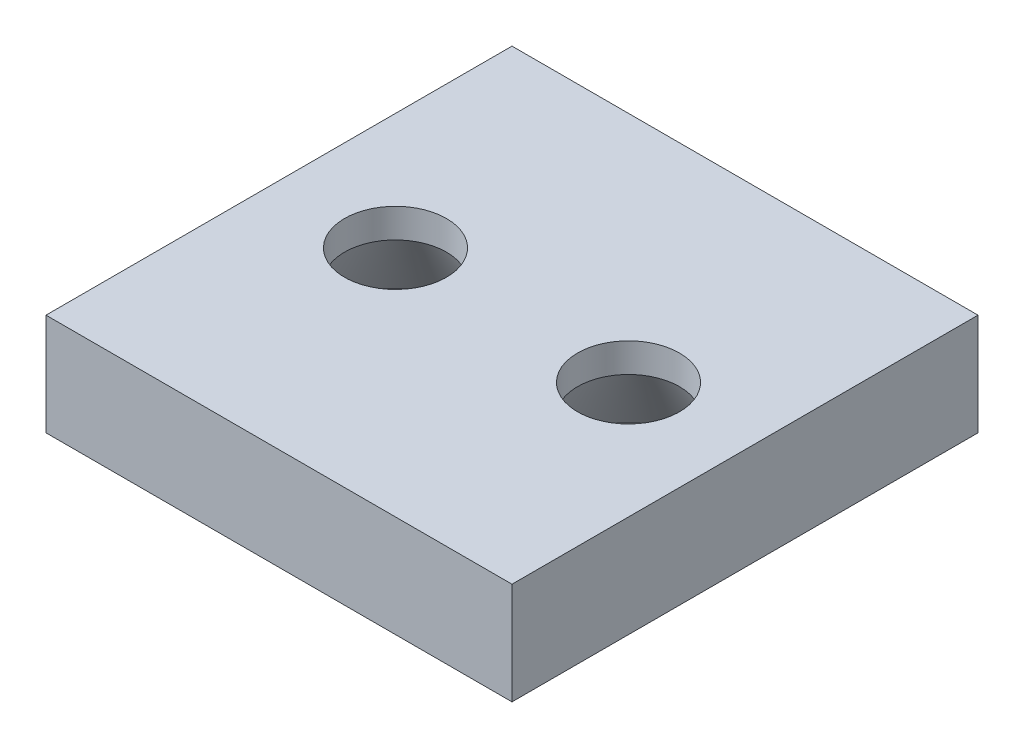
SolidWorks part; units mm, degrees
ref_plane "Front Plane" through (0, 0, 0) normal (0, 0, 1) x (1, 0, 0)
ref_plane "Top Plane" through (0, 0, 0) normal (0, 1, 0) x (1, 0, 0)
ref_plane "Right Plane" through (0, 0, 0) normal (1, 0, 0) x (0, 0, -1)
sketch "Sketch1" plane through (0, 0, 0) normal (0, 1, 0) x (1, 0, 0)
  line L1 (-16, 16) -> (16, 16)
  line L2 (-16, 16) -> (-16, -16)
  line L3 (-16, -16) -> (16, -16)
  line L4 (16, 16) -> (16, -16)
  line L5 (-16, 16) -> (16, -16) construction
  line L6 (-16, -16) -> (16, 16) construction
  point P0 (0, 0)
  dimension "D1" = 32
  dimension "D2" = 32
extrude "Boss-Extrude2" add sketch "Sketch1" along normal blind 7 contours L2 L3 L4 L1
hole_wizard "CSK for M2 Flat Head Machine Screw1" positions "3DSketch1" profile "Sketch2" countersink size "M2" standard "ANSI Metric"
sketch3d "3DSketch1"
  line L0 (16, 0, -16) -> (16, 0, 16) construction
  point P0 (8, 0, 0)
  point P5 (0, 0, 0)
  dimension "D1" = 8
sketch "Sketch2" plane through (8, 0, 0) normal (1, 0, 0) x (0, 0, -1)
  line L0 (0, 0) -> (0, 18.103)
  line L1 (0, 18.103) -> (3.5, 16)
  line L2 (3.5, 16) -> (3.5, 4.9998)
  line L3 (3.5, 4.9998) -> (6.5, 0)
  line L5 (6.5, 0) -> (0, 0)
  line L6 (-3.5, 4.9998) -> (-6.5, 0) construction
  line L10 (0, 18.103) -> (-3.5, 16) construction
  line L11 (0, -6.35) -> (0, 107.95) construction
  dimension "Hole Dia." = 7
  dimension "Hole Depth" = 16
  dimension "Near C'Sink Dia." = 13
  dimension "Near C'Sink Angle" = 61.93
  dimension "Drill Angle" = 118
pattern_linear "LPattern1" count 2 spacing 16 along (-1, 0, 0) of "CSK for M2 Flat Head Machine Screw1"
